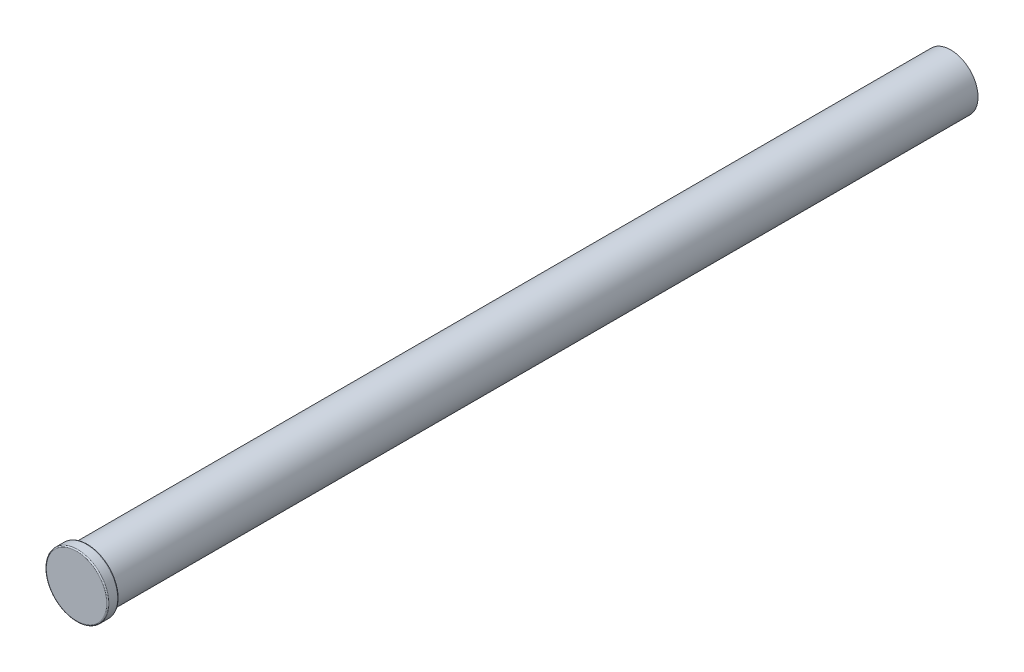
SolidWorks part; units mm, degrees
ref_plane "Front Plane" through (0, 0, 0) normal (0, 0, 1) x (1, 0, 0)
ref_plane "Top Plane" through (0, 0, 0) normal (0, 1, 0) x (1, 0, 0)
ref_plane "Right Plane" through (0, 0, 0) normal (1, 0, 0) x (0, 0, -1)
sketch "Sketch1" plane through (0, 0, 0) normal (0, 0, 1) x (1, 0, 0)
  circle A0 centre (0, 0) radius 9
  dimension "D1" = 18
extrude "Boss-Extrude1" add sketch "Sketch1" along normal blind 80
sketch "Sketch2" plane through (0, 0, 0) normal (0, 0, -1) x (-1, 0, 0)
  circle A0 centre (0, 0) radius 2
  dimension "D1" = 4
extrude "Cut-Extrude1" cut sketch "Sketch2" against normal blind 15
sketch "Sketch3" plane through (0, 0, 0) normal (0, 0, -1) x (-1, 0, 0)
  circle A0 centre (0, 0) radius 1.5
  circle A1 centre (0, 0) radius 9
  circle A3 centre (0, 0) radius 2.5
  circle M4 centre (0, 0) radius 9
  dimension "D1" = 3
  dimension "D2" = 5
extrude "Cut-Extrude3" cut sketch "Sketch3" against normal blind 112 contours A3 M4
sketch "Sketch6" plane through (0, 0, 80) normal (0, 0, 1) x (1, 0, 0)
  circle A0 centre (0, 0) radius 2.8603
extrude "Boss-Extrude2" add sketch "Sketch6" against normal blind 1
fillet "Fillet1" radius 0.1 3 edges at (2.5, 0, 79) (2.8603, 0, 80) (2.8603, 0, 79)
